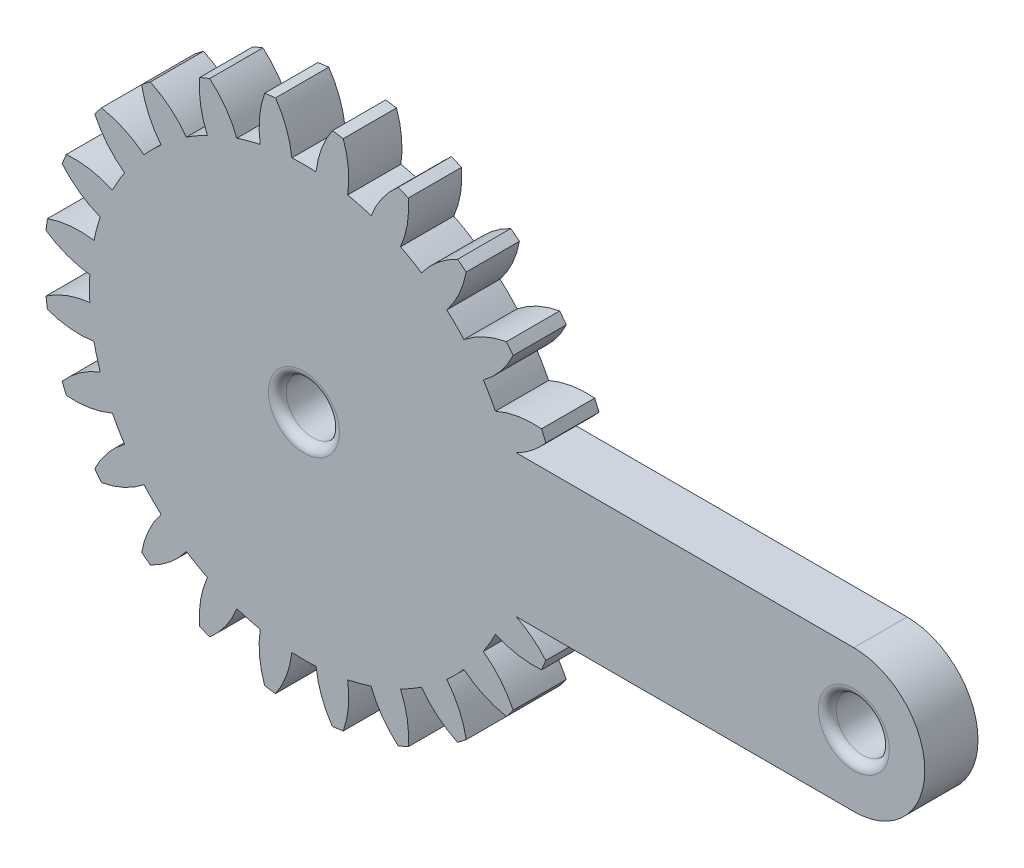
SolidWorks part; units mm, degrees
ref_plane "Front Plane" through (0, 0, 0) normal (0, 0, 1) x (1, 0, 0)
ref_plane "Top Plane" through (0, 0, 0) normal (0, 1, 0) x (1, 0, 0)
ref_plane "Right Plane" through (0, 0, 0) normal (1, 0, 0) x (0, 0, -1)
sketch "Sketch1" plane through (0, 0, 0) normal (0, 0, 1) x (1, 0, 0)
  line L0 (0, 18.4198) -> (0, -12.09) construction
  line L1 (-19.3129, 0) -> (17.8594, 0) construction
  line L2 (0, 0) -> (-0.5167, 3.9247) construction
  line L3 (0, 0) -> (0.5167, 3.9247) construction
  line L4 (31, 4) -> (11.968, 4)
  line L5 (31, -4) -> (11.968, -4)
  line L6 (0, 0) -> (-0.6821, 12.0707) construction
  line L7 (0, 0) -> (0.8332, 4) construction
  line L8 (0, 0) -> (-0.6821, 12.0707) construction
  line L9 (0, 0) -> (-3.783, 11.4829) construction
  line L10 (1.5781, 11.9866) -> (2.3463, 17.822) construction
  line L11 (-1.5781, 11.9866) -> (-2.3403, 17.776) construction
  line L12 (0, -14.63) -> (0, -17.9711) construction
  arc A0 (3.783, 11.4829) -> (2.4653, 11.836) centre (0, 0) ccw
  arc A1 (-11.4155, 9.1501) -> (-11.7929, 8.6583) centre (0, 0) ccw
  arc A2 (31, -4) -> (31, 4) centre (31, 0) ccw
  circle A3 centre (31, 0) radius 1.5
  circle A4 centre (0, 0) radius 1.5
  arc A5 (-2.2165, 14.4611) -> (-2.4653, 11.836) centre (2.8723, 12.6545) ccw
  arc A6 (-1.6018, 14.542) -> (-0.6821, 12.0707) centre (-6.0497, 11.4799) cw
  arc A7 (2.2165, 14.4611) -> (2.4653, 11.836) centre (-2.8723, 12.6545) cw
  arc A8 (1.6018, 14.542) -> (0.6821, 12.0707) centre (6.0497, 11.4799) ccw
  arc A9 (2.2165, 14.4611) -> (2.4653, 11.836) centre (-2.8723, 12.6545) cw
  arc A10 (1.6018, 14.542) -> (0.6821, 12.0707) centre (6.0497, 11.4799) ccw
  arc A11 (5.8838, 13.3947) -> (5.4447, 10.7946) centre (0.5008, 12.9667) cw
  arc A12 (5.311, 13.6319) -> (3.783, 11.4829) centre (8.8147, 9.5229) ccw
  arc A13 (9.1501, 11.4155) -> (8.053, 9.0176) centre (3.8397, 12.3953) cw
  arc A14 (8.6583, 11.7929) -> (6.6261, 10.1125) centre (10.9791, 6.917) ccw
  arc A15 (11.7929, 8.6583) -> (10.1125, 6.6261) centre (6.917, 10.9791) cw
  arc A16 (11.4155, 9.1501) -> (9.0176, 8.053) centre (12.3953, 3.8397) ccw
  arc A17 (13.6319, 5.311) -> (11.968, 4) centre (9.5229, 8.8147) cw
  arc A18 (13.3947, 5.8838) -> (10.7946, 5.4447) centre (12.9667, 0.5008) ccw
  arc A19 (-5.311, 13.6319) -> (-3.783, 11.4829) centre (-8.8147, 9.5229) cw
  arc A20 (-5.8838, 13.3947) -> (-5.4447, 10.7946) centre (-0.5008, 12.9667) ccw
  arc A21 (-8.6583, 11.7929) -> (-6.6261, 10.1125) centre (-10.9791, 6.917) cw
  arc A22 (-9.1501, 11.4155) -> (-8.053, 9.0176) centre (-3.8397, 12.3953) ccw
  arc A23 (-11.4155, 9.1501) -> (-9.0176, 8.053) centre (-12.3953, 3.8397) cw
  arc A24 (-11.7929, 8.6583) -> (-10.1125, 6.6261) centre (-6.917, 10.9791) ccw
  arc A25 (-13.3947, 5.8838) -> (-10.7946, 5.4447) centre (-12.9667, 0.5008) cw
  arc A26 (-13.6319, 5.311) -> (-11.4829, 3.783) centre (-9.5229, 8.8147) ccw
  arc A27 (-14.4611, 2.2165) -> (-11.836, 2.4653) centre (-12.6545, -2.8723) cw
  arc A28 (-14.542, 1.6018) -> (-12.0707, 0.6821) centre (-11.4799, 6.0497) ccw
  arc A29 (-14.542, -1.6018) -> (-12.0707, -0.6821) centre (-11.4799, -6.0497) cw
  arc A30 (-14.4611, -2.2165) -> (-11.836, -2.4653) centre (-12.6545, 2.8723) ccw
  arc A31 (-13.6319, -5.311) -> (-11.4829, -3.783) centre (-9.5229, -8.8147) cw
  arc A32 (-13.3947, -5.8838) -> (-10.7946, -5.4447) centre (-12.9667, -0.5008) ccw
  arc A33 (-11.7929, -8.6583) -> (-10.1125, -6.6261) centre (-6.917, -10.9791) cw
  arc A34 (-11.4155, -9.1501) -> (-9.0176, -8.053) centre (-12.3953, -3.8397) ccw
  arc A35 (-9.1501, -11.4155) -> (-8.053, -9.0176) centre (-3.8397, -12.3953) cw
  arc A36 (-8.6583, -11.7929) -> (-6.6261, -10.1125) centre (-10.9791, -6.917) ccw
  arc A37 (-5.8838, -13.3947) -> (-5.4447, -10.7946) centre (-0.5008, -12.9667) cw
  arc A38 (-5.311, -13.6319) -> (-3.783, -11.4829) centre (-8.8147, -9.5229) ccw
  arc A39 (-2.2165, -14.4611) -> (-2.4653, -11.836) centre (2.8723, -12.6545) cw
  arc A40 (-1.6018, -14.542) -> (-0.6821, -12.0707) centre (-6.0497, -11.4799) ccw
  arc A41 (1.6018, -14.542) -> (0.6821, -12.0707) centre (6.0497, -11.4799) cw
  arc A42 (2.2165, -14.4611) -> (2.4653, -11.836) centre (-2.8723, -12.6545) ccw
  arc A43 (5.311, -13.6319) -> (3.783, -11.4829) centre (8.8147, -9.5229) cw
  arc A44 (5.8838, -13.3947) -> (5.4447, -10.7946) centre (0.5008, -12.9667) ccw
  arc A45 (8.6583, -11.7929) -> (6.6261, -10.1125) centre (10.9791, -6.917) cw
  arc A46 (9.1501, -11.4155) -> (8.053, -9.0176) centre (3.8397, -12.3953) ccw
  arc A47 (11.4155, -9.1501) -> (9.0176, -8.053) centre (12.3953, -3.8397) cw
  arc A48 (11.7929, -8.6583) -> (10.1125, -6.6261) centre (6.917, -10.9791) ccw
  arc A49 (13.3947, -5.8838) -> (10.7946, -5.4447) centre (12.9667, -0.5008) cw
  arc A50 (13.6319, -5.311) -> (11.968, -4) centre (9.5229, -8.8147) ccw
  arc A51 (-8.6583, 11.7929) -> (-9.1501, 11.4155) centre (0, 0) ccw
  arc A52 (-13.3947, 5.8838) -> (-13.6319, 5.311) centre (0, 0) ccw
  arc A53 (-14.4611, 2.2165) -> (-14.542, 1.6018) centre (0, 0) ccw
  arc A54 (-14.542, -1.6018) -> (-14.4611, -2.2165) centre (0, 0) ccw
  arc A55 (0.6821, 12.0707) -> (-0.6821, 12.0707) centre (0, 0) ccw
  arc A56 (-5.4447, 10.7946) -> (-6.6261, 10.1125) centre (0, 0) ccw
  arc A57 (-8.053, 9.0176) -> (-9.0176, 8.053) centre (0, 0) ccw
  arc A58 (-10.1125, 6.6261) -> (-10.7946, 5.4447) centre (0, 0) ccw
  arc A59 (-11.4829, 3.783) -> (-11.836, 2.4653) centre (0, 0) ccw
  arc A60 (-2.4653, 11.836) -> (-3.783, 11.4829) centre (0, 0) ccw
  arc A61 (6.6261, 10.1125) -> (5.4447, 10.7946) centre (0, 0) ccw
  arc A62 (9.0176, 8.053) -> (8.053, 9.0176) centre (0, 0) ccw
  arc A63 (10.7946, 5.4447) -> (10.1125, 6.6261) centre (0, 0) ccw
  arc A64 (-13.6319, -5.311) -> (-13.3947, -5.8838) centre (0, 0) ccw
  arc A65 (10.1125, -6.6261) -> (10.7946, -5.4447) centre (0, 0) ccw
  arc A66 (8.053, -9.0176) -> (9.0176, -8.053) centre (0, 0) ccw
  arc A67 (5.4447, -10.7946) -> (6.6261, -10.1125) centre (0, 0) ccw
  arc A68 (2.4653, -11.836) -> (3.783, -11.4829) centre (0, 0) ccw
  arc A69 (-0.6821, -12.0707) -> (0.6821, -12.0707) centre (0, 0) ccw
  arc A70 (-3.783, -11.4829) -> (-2.4653, -11.836) centre (0, 0) ccw
  arc A71 (-12.0707, 0.6821) -> (-12.0707, -0.6821) centre (0, 0) ccw
  arc A72 (-11.836, -2.4653) -> (-11.4829, -3.783) centre (0, 0) ccw
  arc A73 (-9.0176, -8.053) -> (-8.053, -9.0176) centre (0, 0) ccw
  arc A74 (-6.6261, -10.1125) -> (-5.4447, -10.7946) centre (0, 0) ccw
  arc A75 (-11.7929, -8.6583) -> (-11.4155, -9.1501) centre (0, 0) ccw
  arc A76 (-9.1501, -11.4155) -> (-8.6583, -11.7929) centre (0, 0) ccw
  arc A77 (-5.8838, -13.3947) -> (-5.311, -13.6319) centre (0, 0) ccw
  arc A78 (-2.2165, -14.4611) -> (-1.6018, -14.542) centre (0, 0) ccw
  arc A79 (1.6018, -14.542) -> (2.2165, -14.4611) centre (0, 0) ccw
  arc A80 (5.311, -13.6319) -> (5.8838, -13.3947) centre (0, 0) ccw
  arc A81 (8.6583, -11.7929) -> (9.1501, -11.4155) centre (0, 0) ccw
  arc A82 (11.4155, -9.1501) -> (11.7929, -8.6583) centre (0, 0) ccw
  arc A83 (13.3947, -5.8838) -> (13.6319, -5.311) centre (0, 0) ccw
  arc A84 (-10.7946, -5.4447) -> (-10.1125, -6.6261) centre (0, 0) ccw
  arc A85 (13.6319, 5.311) -> (13.3947, 5.8838) centre (0, 0) ccw
  arc A86 (11.7929, 8.6583) -> (11.4155, 9.1501) centre (0, 0) ccw
  arc A87 (9.1501, 11.4155) -> (8.6583, 11.7929) centre (0, 0) ccw
  arc A88 (5.8838, 13.3947) -> (5.311, 13.6319) centre (0, 0) ccw
  arc A89 (2.2165, 14.4611) -> (-5.8838, 13.3947) centre (0, 0) ccw
  point P21 (-1.9096, 14.5048)
  point P24 (-1.5781, 11.9866)
  point P25 (-1.9095, 14.5038)
  dimension "D1" = 29.26
  dimension "D2" = 24.18
  dimension "D5" = 8
  dimension "D7" = 3
  dimension "D14" = 5.4
  dimension "D3" = 15
  dimension "D4" = 7.5
  dimension "D6" = 31
  dimension "D8" = 0.62
  dimension "D9" = 1.7986
  dimension "D11" = 15
  dimension "D13" = 15
  dimension "D10" = 6
  dimension "D12" = 17
extrude "Boss-Extrude1" add sketch "Sketch1" against normal blind 3 contours A7 A89 A8 A55 A6 A5 A60 A19 A20 A56 A21 A51 A22 A57 A23 A1 A24 A58 A25 A52 A26 A59 A27 A53 A28 A71 A29 A54 A30 A72 A33 A75 A34 A73 A35 A76 A36 A74 A37 A77 A38 A70 A39 A78 A40 A69 A41
fillet "Fillet1" radius 0.5 4 edges at (32.5, 0, 0) (32.5, 0, -3) (1.5, 0, 0) (1.5, 0, -3)
